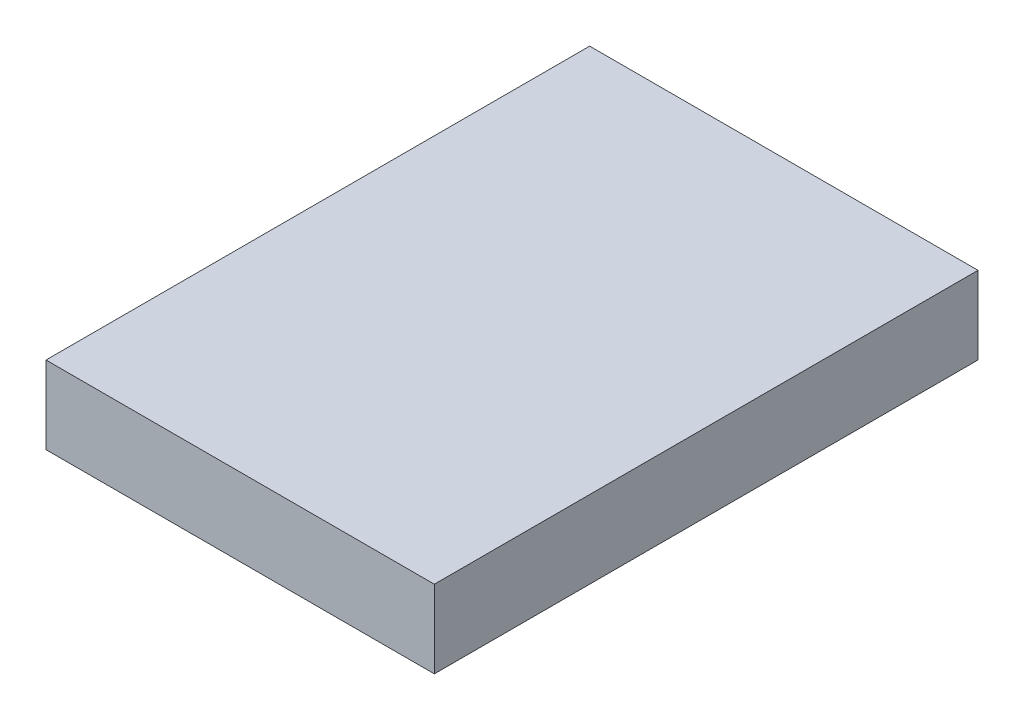
SolidWorks part; units mm, degrees
ref_plane "前视基准面" through (0, 0, 0) normal (0, 0, 1) x (1, 0, 0)
ref_plane "上视基准面" through (0, 0, 0) normal (0, 1, 0) x (1, 0, 0)
ref_plane "右视基准面" through (0, 0, 0) normal (1, 0, 0) x (0, 0, -1)
sketch "草图1" plane through (0, 0, 0) normal (0, 1, 0) x (1, 0, 0)
  line L1 (-25, 35) -> (25, 35)
  line L2 (-25, 35) -> (-25, -35)
  line L3 (-25, -35) -> (25, -35)
  line L4 (25, 35) -> (25, -35)
  line L5 (-25, 35) -> (25, -35) construction
  line L6 (-25, -35) -> (25, 35) construction
  point P0 (0, 0)
  dimension "D1" = 70
  dimension "D2" = 50
extrude "凸台-拉伸1" add sketch "草图1" along normal blind 10
